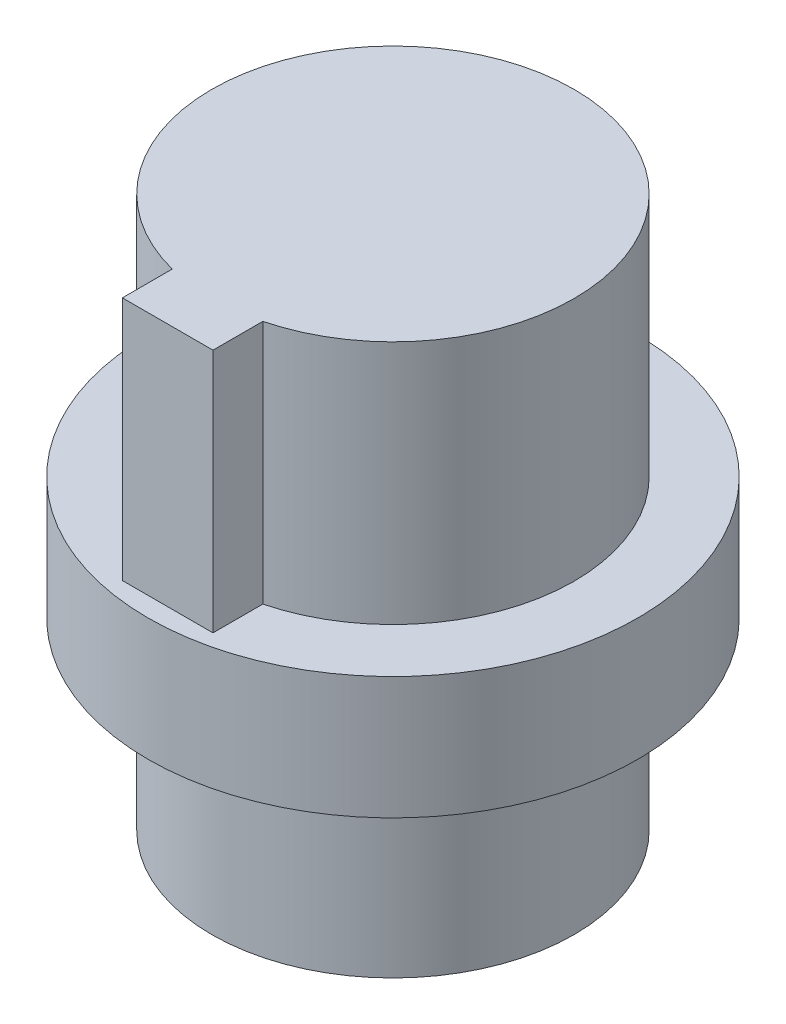
SolidWorks part; units mm, degrees
ref_plane "Front Plane" through (0, 0, 0) normal (0, 0, 1) x (1, 0, 0)
ref_plane "Top Plane" through (0, 0, 0) normal (0, 1, 0) x (1, 0, 0)
ref_plane "Right Plane" through (0, 0, 0) normal (1, 0, 0) x (0, 0, -1)
sketch "Sketch1" plane through (0, 0, 0) normal (0, 1, 0) x (1, 0, 0)
  circle A0 centre (0, 0) radius 9.398
  dimension "D1" = 18.796
extrude "Boss-Extrude1" add sketch "Sketch1" along normal blind 9.525
ref_plane "Plane1" through (0, 0, 11.684) normal (0, 0, 1) x (1, 0, 0)
sketch "Sketch2" plane through (0, 9.525, 0) normal (0, 1, 0) x (1, 0, 0)
  circle A0 centre (0, 0) radius 12.7
  dimension "D1" = 25.4
extrude "Boss-Extrude2" add sketch "Sketch2" along normal blind 6.35
sketch "Sketch3" plane through (0, 15.875, 0) normal (0, 1, 0) x (1, 0, 0)
  circle A0 centre (0, 0) radius 9.398
  dimension "D1" = 18.796
extrude "Boss-Extrude3" add sketch "Sketch3" along normal blind 12.7
sketch "Sketch4" plane through (0, 0, 11.684) normal (0, 0, 1) x (1, 0, 0)
  line L0 (12.7, 15.875) -> (-12.7, 15.875) construction
  line L1 (-2.3495, 15.875) -> (2.3495, 15.875)
  line L2 (-2.3495, 15.875) -> (-2.3495, 28.575)
  line L3 (-2.3495, 28.575) -> (2.3495, 28.575)
  line L4 (2.3495, 15.875) -> (2.3495, 28.575)
  line L5 (9.398, 28.575) -> (-9.398, 28.575) construction
  line L6 (0, 0) -> (0, 30.3641) construction
  point P11 (0, 28.575)
  dimension "D1" = 4.699
extrude "Boss-Extrude4" add sketch "Sketch4" against normal up to surface (2.5844 mm away)
